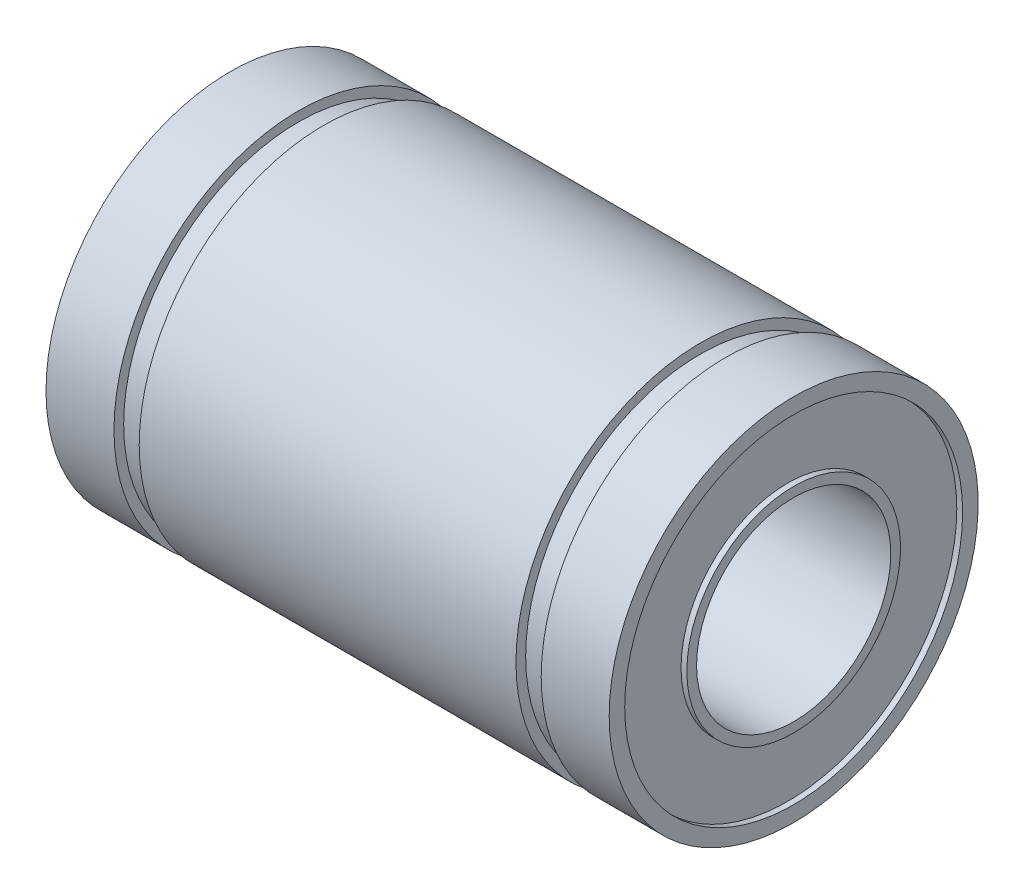
SolidWorks part; units mm, degrees
material "Plain Carbon Steel"
ref_plane "Front Plane" through (0, 0, 0) normal (0, 0, 1) x (1, 0, 0)
ref_plane "Top Plane" through (0, 0, 0) normal (0, 1, 0) x (1, 0, 0)
ref_plane "Right Plane" through (0, 0, 0) normal (1, 0, 0) x (0, 0, -1)
sketch "Sketch1" plane through (0, 0, 0) normal (0, 0, 1) x (1, 0, 0)
  line L0 (-14.5, 0) -> (14.5, 0) construction
  line L1 (-14.5, 5) -> (14.5, 5)
  line L2 (-14.5, 5) -> (-14.5, 5.5)
  line L3 (-14.5, 9.5) -> (-11, 9.5)
  line L4 (14.5, 5) -> (14.5, 5.5)
  line L5 (11, 9.5) -> (14.5, 9.5)
  line L6 (-14.5, 8.7) -> (-14.2, 8.7)
  line L7 (0, 0) -> (0, 1.809) construction
  line L8 (-14.5, 5.5) -> (-14.2, 5.5)
  line L9 (-14.2, 8.7) -> (-14.2, 5.5)
  line L10 (-14.5, 8.7) -> (-14.5, 9.5)
  line L11 (-11, 9.5) -> (-11, 9)
  line L12 (-11, 9) -> (-9.7, 9)
  line L13 (-9.7, 9.5) -> (-9.7, 9)
  line L14 (-9.7, 9.5) -> (9.7, 9.5)
  line L15 (11, 9.5) -> (11, 9)
  line L16 (11, 9) -> (9.7, 9)
  line L17 (9.7, 9.5) -> (9.7, 9)
  line L18 (14.2, 8.7) -> (14.2, 5.5)
  line L19 (14.5, 5.5) -> (14.2, 5.5)
  line L20 (14.5, 8.7) -> (14.2, 8.7)
  line L21 (14.5, 8.7) -> (14.5, 9.5)
  point P21 (14.5, 9.5)
  point P24 (-14.5, 9.5)
  dimension "D1" = 10
  dimension "D2" = 19
  dimension "D3" = 29
  dimension "D4" = 0.5
  dimension "D5" = 0.3
  dimension "D6" = 0.8
  dimension "D7" = 22
  dimension "D8" = 1.3
  dimension "D9" = 18
revolve "Revolve1" add sketch "Sketch1" angle 360 about L0
